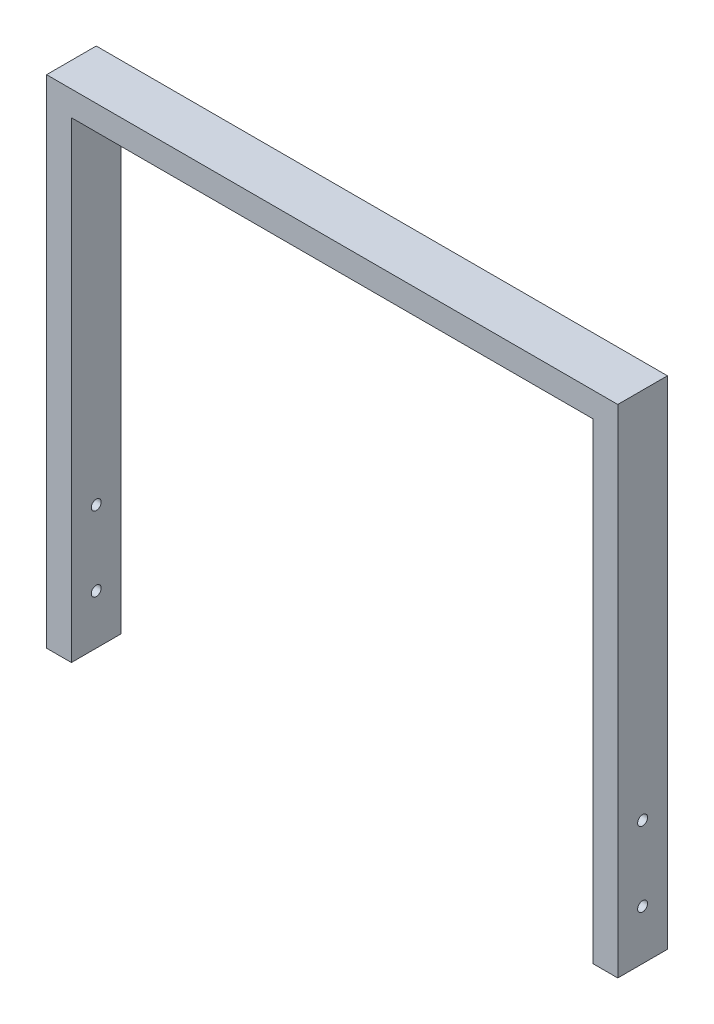
SolidWorks part; units mm, degrees
ref_plane "Front Plane" through (0, 0, 0) normal (0, 0, 1) x (1, 0, 0)
ref_plane "Top Plane" through (0, 0, 0) normal (0, 1, 0) x (1, 0, 0)
ref_plane "Right Plane" through (0, 0, 0) normal (1, 0, 0) x (0, 0, -1)
sketch "Sketch1" plane through (0, 0, 0) normal (0, 0, 1) x (1, 0, 0)
  line L0 (0, 0) -> (0, 200)
  line L1 (0, 200) -> (230, 200)
  line L2 (230, 200) -> (230, 0)
  line L3 (230, 0) -> (220, 0)
  line L4 (220, 0) -> (220, 190)
  line L5 (220, 190) -> (10, 190)
  line L6 (10, 190) -> (10, 0)
  line L7 (10, 0) -> (0, 0)
  dimension "D1" = 230
  dimension "D2" = 10
  dimension "D3" = 10
  dimension "D4" = 10
  dimension "D5" = 200
extrude "Boss-Extrude1" add sketch "Sketch1" along normal mid plane 20
sketch "Sketch2" plane through (0, 0, 0) normal (-1, 0, 0) x (0, 0, 1)
  circle A0 centre (0, 20) radius 2
  circle A1 centre (0, 50) radius 2
  dimension "D3" = 4
  dimension "D1" = 20
  dimension "D2" = 30
extrude "Cut-Extrude1" cut sketch "Sketch2" against normal through all
